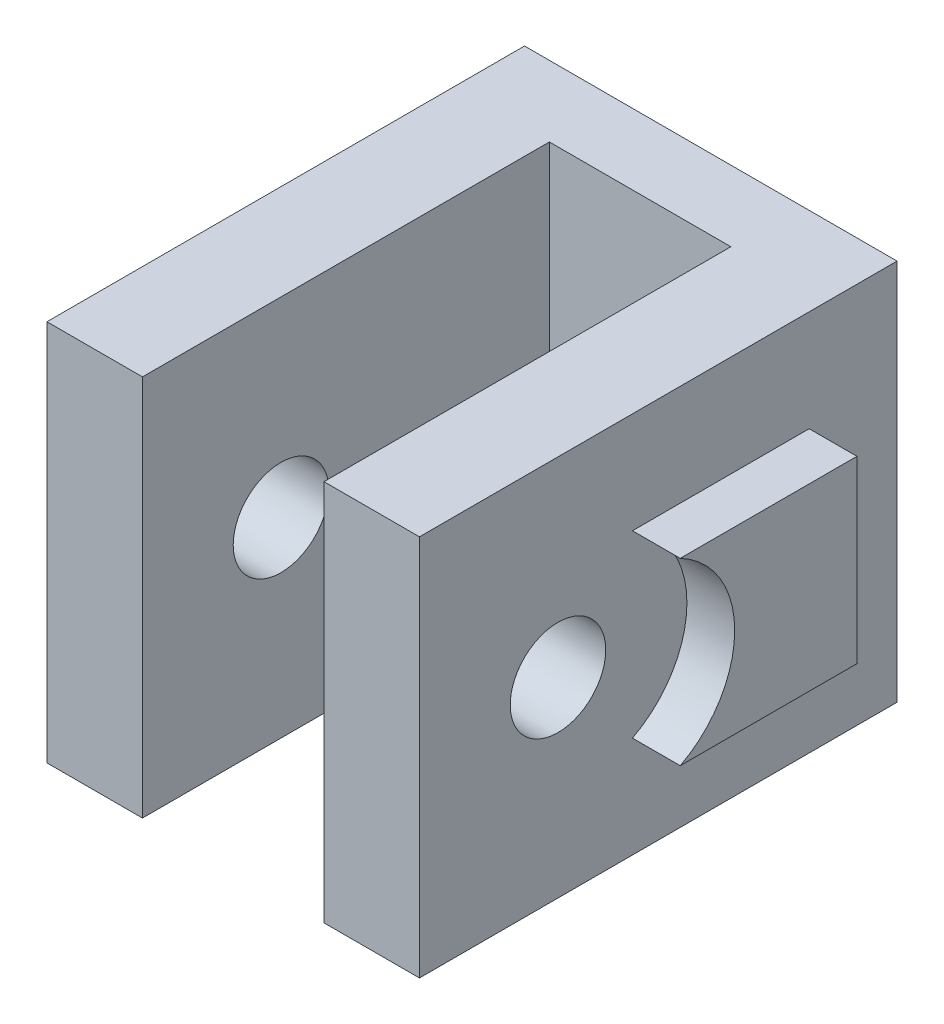
SolidWorks part; units mm, degrees
ref_plane "Front Plane" through (0, 0, 0) normal (0, 0, 1) x (1, 0, 0)
ref_plane "Top Plane" through (0, 0, 0) normal (0, 1, 0) x (1, 0, 0)
ref_plane "Right Plane" through (0, 0, 0) normal (1, 0, 0) x (0, 0, -1)
sketch "Sketch1" plane through (0, 0, 0) normal (0, 1, 0) x (1, 0, 0)
  line L0 (14.5, -25) -> (19.5, -25)
  line L1 (0, 0) -> (19.5, 0)
  line L2 (0, 0) -> (0, -25)
  line L3 (0, -25) -> (5, -25)
  line L4 (19.5, 0) -> (19.5, -25)
  line L6 (5, -25) -> (5, -3.7)
  line L7 (5, -3.7) -> (14.5, -3.7)
  line L8 (14.5, -25) -> (14.5, -3.7)
  point P9 (9.75, 0)
  point P10 (9.75, -3.7)
  dimension "D1" = 5
  dimension "D2" = 3.7
  dimension "D3" = 19.5
  dimension "D4" = 25
extrude "Boss-Extrude1" add sketch "Sketch1" along normal blind 20
sketch "Sketch2" plane through (0, 0, 3.7) normal (0, 0, 1) x (1, 0, 0)
  point P3 (9.75, 10)
hole_wizard "M5 Tapped Hole1" positions "Sketch3" profile "Sketch4" tap size "M5" standard "AS" end condition through all
sketch "Sketch3" plane through (0, 0, 0) normal (0, 0, -1) x (-1, 0, 0)
  point P0 (-9.75, 10)
  point P17 (-9.75, 10)
sketch "Sketch4" plane through (9.75, 10, 0) normal (1, 0, 0) x (0, 1, 0)
  line L0 (0, 0) -> (0, 25)
  line L1 (0, 25) -> (2.1, 25)
  line L2 (2.1, 25) -> (2.1, 0)
  line L5 (2.1, 0) -> (0, 0)
  line L11 (0, -6.35) -> (0, 107.95) construction
  dimension "Thru Tap Drill Dia." = 4.2
  dimension "Thru Tap Drill Depth" = 25
sketch "Sketch5" plane through (19.5, 0, 0) normal (1, 0, 0) x (0, 0, -1)
  line L0 (-25, 20) -> (-25, 0) construction
  circle A0 centre (-17.75, 10) radius 2.5
  dimension "D1" = 5
  dimension "D2" = 7.25
extrude "Cut-Extrude1" cut sketch "Sketch5" against normal through all
sketch "Sketch6" plane through (19.5, 0, 0) normal (1, 0, 0) x (0, 0, -1)
  line L0 (-25, 20) -> (-25, 0) construction
  line L1 (-13.85, 14.7) -> (-4.6, 14.7)
  line L3 (-13.85, 5.3) -> (-4.6, 5.3)
  line L4 (-4.6, 14.7) -> (-4.6, 5.3)
  line L5 (-13.85, 14.7) -> (-4.6, 5.3) construction
  line L6 (-13.85, 5.3) -> (-4.6, 14.7) construction
  arc A0 (-13.85, 5.3) -> (-13.85, 14.7) centre (-16.2995, 10) ccw
  point P0 (-9.225, 10)
  dimension "D4" = 5.3
  dimension "D1" = 20.4
  dimension "D2" = 9.4
  dimension "D3" = 9.25
extrude "Boss-Extrude2" add sketch "Sketch6" along normal blind 2.5 contours L1 L4 L3 A0
ref_plane "Plane1" through (9.75, 0, 0) normal (1, 0, 0) x (0, 0, -1)
mirror "Mirror1" about plane through (9.75, 0, 0) normal (1, 0, 0) of "Boss-Extrude2"
